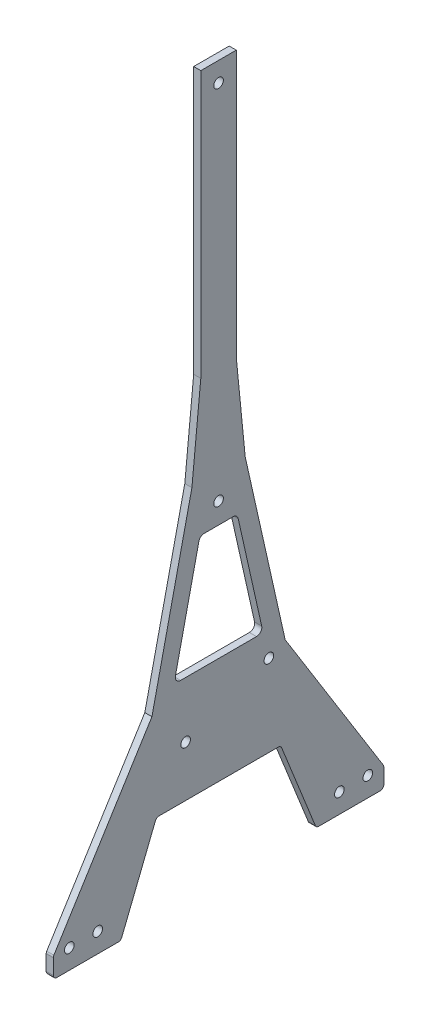
SolidWorks part; units mm, degrees
ref_plane "前基準面" through (0, 0, 0) normal (0, 0, 1) x (1, 0, 0)
ref_plane "上基準面" through (0, 0, 0) normal (0, 1, 0) x (1, 0, 0)
ref_plane "右基準面" through (0, 0, 0) normal (1, 0, 0) x (0, 0, -1)
sketch "草圖1" plane through (0, 0, 0) normal (1, 0, 0) x (0, 0, -1)
  line L0 (55, 0) -> (-55, 0) construction
  line L1 (-100, 0) -> (100, 0) construction
  line L2 (-100, 0) -> (-100, 401.53) construction
  line L3 (-100, 401.53) -> (100, 401.53) construction
  line L4 (100, 0) -> (100, 401.53) construction
  line L5 (0, 55) -> (0, -55) construction
  line L6 (-84, 11) -> (-68, 11) construction
  line L7 (-100, 0) -> (100, 0) construction
  line L8 (-100, 0) -> (-100, 100.38) construction
  line L9 (-100, 100.38) -> (100, 100.38) construction
  line L10 (100, 0) -> (100, 100.38) construction
  line L11 (-100, 0) -> (100, 0) construction
  line L12 (-100, 0) -> (-100, 200.76) construction
  line L13 (-100, 200.76) -> (100, 200.76) construction
  line L14 (100, 0) -> (100, 200.76) construction
  line L15 (-100, 0) -> (-55, 0) construction
  line L19 (-55, 0) -> (-35, 50)
  line L20 (-55, 0) -> (55, 0)
  line L21 (-55, 0) -> (-55, 50)
  line L22 (-55, 50) -> (55, 50)
  line L23 (55, 0) -> (55, 50)
  line L24 (55, 0) -> (35, 50)
  line L25 (-37.5, 100.38) -> (37.5, 100.38)
  line L26 (-100, 0) -> (-37.5, 100.38)
  line L27 (37.5, 100.38) -> (100, 0)
  line L28 (-15, 200.76) -> (15, 200.76)
  line L29 (-37.5, 100.38) -> (-15, 200.76)
  line L30 (15, 200.76) -> (37.5, 100.38)
  line L32 (-15, 200.76) -> (15, 200.76)
  line L33 (-15, 200.76) -> (-15, 401.53)
  line L34 (-15, 401.53) -> (15, 401.53)
  line L35 (15, 200.76) -> (15, 401.53)
  line L36 (55, 0) -> (100, 0)
  line L37 (-23.4214, 91.6371) -> (23.4214, 109.1229)
  line L38 (-23.4214, 91.6371) -> (23.4214, 109.1229)
  line L39 (-23.4214, 91.6371) -> (-18.5253, 78.5211)
  line L40 (23.4214, 109.1229) -> (28.3174, 96.0069)
  line L41 (-18.5253, 78.5211) -> (28.3174, 96.0069)
  line L42 (68, 0) -> (84, 0) construction
  line L43 (68, 0) -> (68, 11) construction
  line L44 (68, 11) -> (84, 11) construction
  line L45 (84, 0) -> (84, 11) construction
  line L47 (-110, 0) -> (-55, 0)
  line L48 (55, 0) -> (100, 0)
  line L49 (-15, 200.76) -> (-10, 251.53)
  line L50 (-10, 401.53) -> (10, 401.53)
  line L51 (-10, 401.53) -> (-10, 251.53)
  line L52 (-10, 251.53) -> (10, 251.53)
  line L53 (10, 401.53) -> (10, 251.53)
  line L54 (10, 251.53) -> (15, 200.76)
  line L56 (-100, 0) -> (-93, 0)
  line L57 (-100, 0) -> (-100, 20)
  line L58 (-100, 20) -> (-93, 20)
  line L59 (-93, 0) -> (-93, 20)
  line L60 (100, 0) -> (93, 0)
  line L61 (100, 0) -> (100, 20)
  line L62 (100, 20) -> (93, 20)
  line L63 (93, 0) -> (93, 20)
  circle A4 centre (-18.5253, 78.5211) radius 2.7
  circle A5 centre (28.3174, 96.0069) radius 2.7
  circle A6 centre (0, 186.76) radius 2.7
  circle A7 centre (0, 390.53) radius 2.7
  circle A8 centre (68, 11) radius 2.7
  circle A9 centre (84, 11) radius 2.7
  circle A10 centre (-84, 11) radius 2.7
  circle A11 centre (-68, 11) radius 2.7
  point P36 (0, 100.38)
  dimension "D9" = 11
  dimension "D10" = 16
  dimension "D19" = 14
  dimension "D20" = 5.4
  dimension "D21" = 5.4
  dimension "D22" = 5.4
  dimension "D24" = 5.4
  dimension "D6" = 5.4
  dimension "D7" = 5.4
  dimension "D1" = 200
  dimension "D2" = 100
  dimension "D3" = 401.53
  dimension "D4" = 100.38
  dimension "D5" = 200.76
  dimension "D8" = 2
  dimension "D11" = 110
  dimension "D12" = 55
  dimension "D13" = 75
  dimension "D14" = 37.5
  dimension "D15" = 30
  dimension "D16" = 15
  dimension "D17" = 20.47
  dimension "D18" = 50
  dimension "D23" = 14
  dimension "D25" = 11
  dimension "D26" = 68
  dimension "D27" = 10
  dimension "D28" = 50
  dimension "D29" = 20
  dimension "D30" = 10
  dimension "D31" = 150
  dimension "D32" = 20
  dimension "D33" = 7
  dimension "D34" = 20
  dimension "D35" = 7
extrude "填料-伸長1" add sketch "草圖1" along normal blind 4 contours L53 L34 L51 L52 A7 | L54 L52 L49 L28 | L37 L40 L25 L30 L28 L29 A6 | A5 L40 L25 L37 L39 A4 L41 | L40 L37 L25 | A5 L41 A4 L39 L37 L25 L26 L47 L21 L22 L23 L36 L27 L40 A11 A10 A9 A8 | L22 L21 L19 | L24 L23 L22
sketch "草圖3" plane through (4, 0, 0) normal (1, 0, 0) x (0, 0, -1)
  line L9 (-27.7421, 98.1928) -> (-5.2421, 198.5728)
  line L10 (-27.7421, 98.1928) -> (-5.2421, 198.5728)
  line L11 (-5.2421, 198.5728) -> (5.2421, 198.5728)
  line L12 (5.2421, 198.5728) -> (27.7421, 98.1928)
  line L13 (5.2421, 198.5728) -> (27.7421, 98.1928)
  line L14 (-27.7421, 98.1928) -> (27.7421, 98.1928)
  line L15 (-25.0956, 110) -> (25.0956, 110)
  line L16 (-10.5259, 175) -> (10.5259, 175)
  line L17 (2.2, 0) -> (-2.2, 0) construction
  dimension "D3" = 110
  dimension "D4" = 175
  dimension "D1" = 10
  dimension "D2" = 10
extrude "除料-伸長1" cut sketch "草圖3" against normal up to next contours L16 L10 L15 L13
fillet "圓角1" radius 3 4 edges at (2, 110, -25.0956) (2, 110, 25.0956) (2, 175, 10.5259) (2, 175, -10.5259)
fillet "圓角2" radius 2 8 edges at (2, 0, 93) (2, 11.2426, 93) (2, 0, -93) (2, 11.2426, -93) (2, 0, -55) (2, 50, -35) (2, 0, 55) (2, 50, 35)
